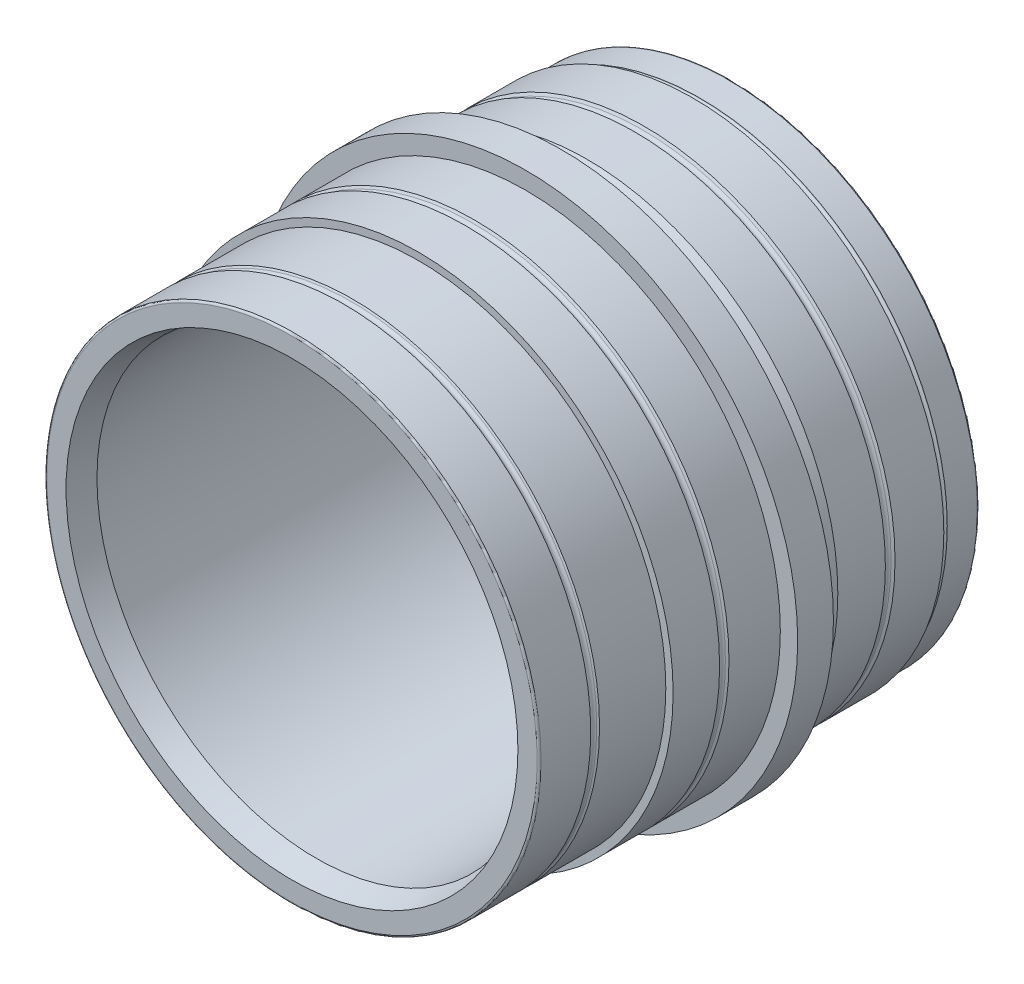
SolidWorks part; units mm, degrees
material "OVAKO 280 HB"
ref_plane "Front Plane" through (0, 0, 0) normal (0, 0, 1) x (1, 0, 0)
ref_plane "Top Plane" through (0, 0, 0) normal (0, 1, 0) x (1, 0, 0)
ref_plane "Right Plane" through (0, 0, 0) normal (1, 0, 0) x (0, 0, -1)
sketch "Sketch1" plane through (0, 0, 0) normal (1, 0, 0) x (0, 0, -1)
  line L0 (0, 0) -> (45.15, 0) construction
  line L1 (0, 23.1824) -> (2.5, 22.5125)
  line L2 (2.5, 22.5125) -> (42.65, 22.5125)
  line L3 (42.65, 22.5125) -> (45.15, 23.1824)
  line L4 (45.15, 23.1824) -> (45.15, 25.1575)
  line L5 (44.95, 25.3575) -> (41.8803, 25.3575)
  line L6 (41.15, 25.3575) -> (41.15, 25.7325)
  line L7 (41.15, 25.7325) -> (36.1451, 25.7325)
  line L8 (30.275, 25.7325) -> (29.314, 25.475)
  line L9 (29.314, 25.475) -> (28.775, 25.475)
  line L10 (28.275, 25.975) -> (28.275, 26.8375)
  line L11 (28.275, 26.8375) -> (27.6688, 27.8875)
  line L12 (27.6688, 27.8875) -> (24, 27.8875)
  line L13 (24, 27.8875) -> (24, 26.1075)
  line L14 (24, 26.1075) -> (18.7306, 26.1075)
  line L15 (13, 26.1075) -> (13, 25.3575)
  line L16 (13, 25.3575) -> (6.2018, 25.3575)
  line L17 (0, 25.1575) -> (0, 23.1824)
  line L20 (5.2982, 25.3575) -> (5.4036, 25.175)
  line L21 (6.0964, 25.175) -> (6.2018, 25.3575)
  line L22 (17.7694, 26.1075) -> (17.9036, 25.875)
  line L23 (18.5964, 25.875) -> (18.7306, 26.1075)
  line L24 (35.1549, 25.7325) -> (35.3036, 25.475)
  line L25 (35.9964, 25.475) -> (36.1451, 25.7325)
  line L26 (41.15, 25.3575) -> (41.1688, 25.325)
  line L27 (41.8616, 25.325) -> (41.8803, 25.3575)
  line L28 (35.1549, 25.7325) -> (30.275, 25.7325)
  line L29 (17.7694, 26.1075) -> (13, 26.1075)
  line L30 (5.2982, 25.3575) -> (0.2, 25.3575)
  arc A2 (5.4036, 25.175) -> (6.0964, 25.175) centre (5.75, 25.375) ccw
  arc A3 (17.9036, 25.875) -> (18.5964, 25.875) centre (18.25, 26.075) ccw
  arc A4 (35.3036, 25.475) -> (35.9964, 25.475) centre (35.65, 25.675) ccw
  arc A5 (41.1688, 25.325) -> (41.8616, 25.325) centre (41.5152, 25.525) ccw
  arc A6 (28.775, 25.475) -> (28.275, 25.975) centre (28.775, 25.975) cw
  arc A7 (0.2, 25.3575) -> (0, 25.1575) centre (0.2, 25.1575) ccw
  arc A8 (45.15, 25.1575) -> (44.95, 25.3575) centre (44.95, 25.1575) ccw
  dimension "D22" = 60
  dimension "D23" = 50.55
  dimension "D25" = 0.4
  dimension "D26" = 60
  dimension "D28" = 0.4
  dimension "D29" = 51.35
  dimension "D30" = 49.95
  dimension "D21" = 0.4
  dimension "D32" = 0.4
  dimension "D34" = 50.25
  dimension "D36" = 0.5
  dimension "D37" = 0.2
  dimension "D1" = 45.15
  dimension "D2" = 55.775
  dimension "D3" = 50.715
  dimension "D4" = 52.215
  dimension "D5" = 50.715
  dimension "D6" = 51.465
  dimension "D7" = 50.95
  dimension "D8" = 45.025
  dimension "D9" = 30
  dimension "D10" = 1.05
  dimension "D11" = 15
  dimension "D12" = 2
  dimension "D13" = 15
  dimension "D14" = 15
  dimension "D15" = 2.5
  dimension "D16" = 2.5
  dimension "D17" = 13
  dimension "D18" = 24
  dimension "D19" = 16.875
  dimension "D20" = 4
  dimension "D24" = 5.75
  dimension "D27" = 60
  dimension "D31" = 18.25
  dimension "D33" = 60
  dimension "D35" = 9.5
revolve "Revolve1" add sketch "Sketch1" angle 360 about L0
